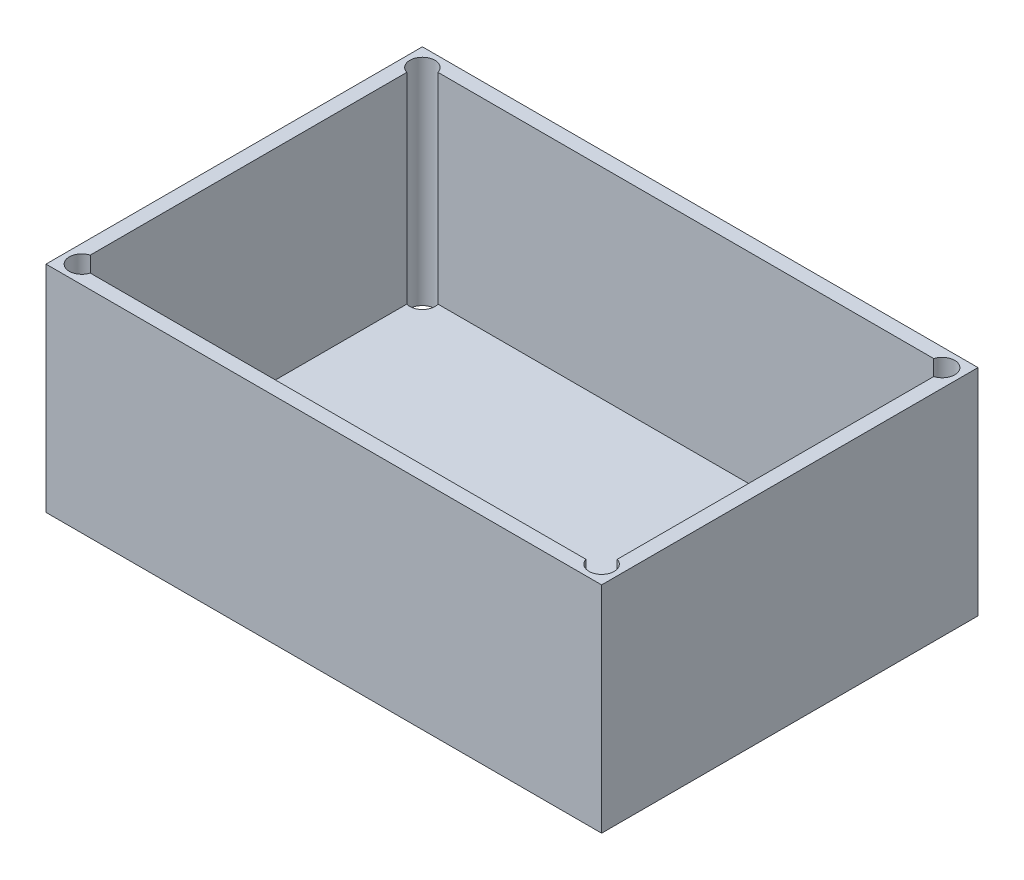
SolidWorks part; units mm, degrees
ref_plane "Alzado" through (0, 0, 0) normal (0, 0, 1) x (1, 0, 0)
ref_plane "Planta" through (0, 0, 0) normal (0, 1, 0) x (1, 0, 0)
ref_plane "Vista lateral" through (0, 0, 0) normal (1, 0, 0) x (0, 0, -1)
sketch "Croquis1" plane through (0, 0, 0) normal (0, 1, 0) x (1, 0, 0)
  line L1 (38.75, -26.25) -> (-38.75, -26.25)
  line L2 (38.75, -26.25) -> (38.75, 26.25)
  line L3 (38.75, 26.25) -> (-38.75, 26.25)
  line L4 (-38.75, -26.25) -> (-38.75, 26.25)
  line L5 (38.75, -26.25) -> (-38.75, 26.25) construction
  line L6 (38.75, 26.25) -> (-38.75, -26.25) construction
  point P0 (0, 0)
  dimension "D1" = 77.5
  dimension "D2" = 52.5
extrude "Saliente-Extruir1" add sketch "Croquis1" along normal blind 30
shell "Vaciado1" thickness 2
sketch "Croquis2" plane through (0, 2, 0) normal (0, 1, 0) x (1, 0, 0)
  line L1 (36.25, -23.75) -> (-36.25, -23.75) construction
  line L2 (36.25, -23.75) -> (36.25, 23.75) construction
  line L3 (36.25, 23.75) -> (-36.25, 23.75) construction
  line L4 (-36.25, -23.75) -> (-36.25, 23.75) construction
  line L5 (36.25, -23.75) -> (-36.25, 23.75) construction
  line L6 (36.25, 23.75) -> (-36.25, -23.75) construction
  circle A1 centre (-36.25, 23.75) radius 1.75
  circle A2 centre (36.25, 23.75) radius 1.75
  circle A3 centre (36.25, -23.75) radius 1.75
  circle A4 centre (-36.25, -23.75) radius 1.75
  point P0 (0, 0)
  dimension "D3" = 3.5
  dimension "D1" = 72.5
  dimension "D2" = 47.5
extrude "Cortar-Extruir1" cut sketch "Croquis2" against normal mid plane 60
